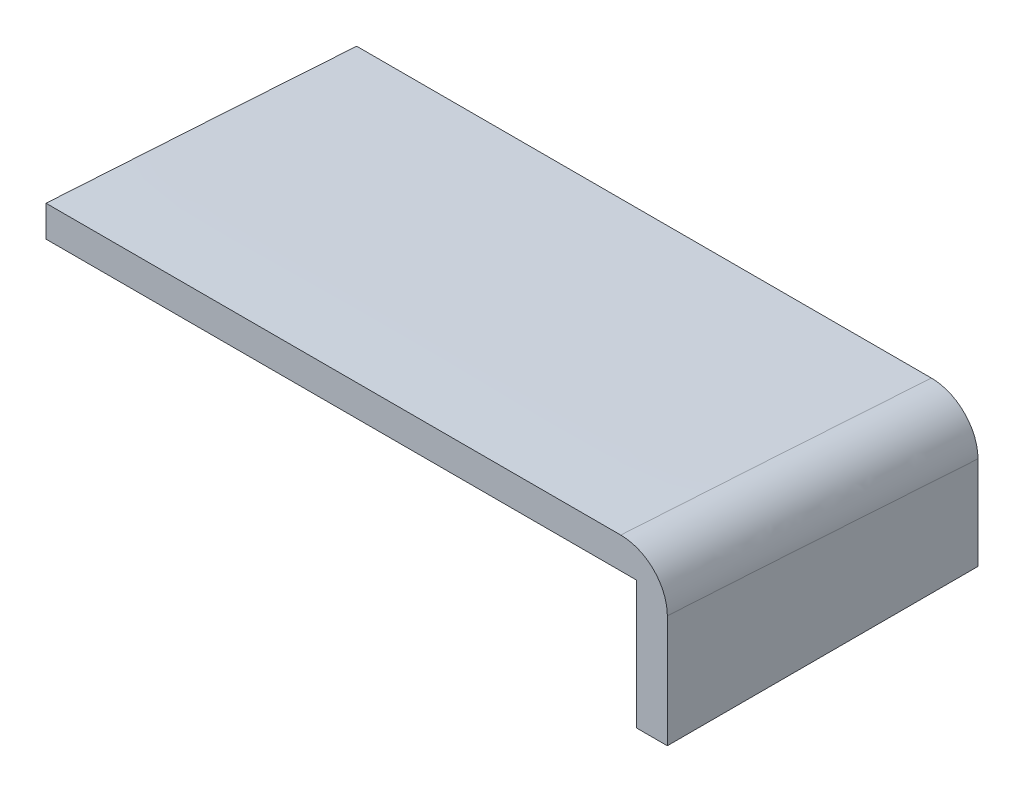
SolidWorks part; units mm, degrees
ref_plane "정면" through (0, 0, 0) normal (0, 0, 1) x (1, 0, 0)
ref_plane "윗면" through (0, 0, 0) normal (0, 1, 0) x (1, 0, 0)
ref_plane "우측면" through (0, 0, 0) normal (1, 0, 0) x (0, 0, -1)
sketch "스케치1" plane through (0, 0, 0) normal (0, 0, 1) x (1, 0, 0)
  line L1 (-40, 50) -> (40, 50)
  line L2 (-40, 50) -> (-40, -50)
  line L3 (-40, -50) -> (40, -50)
  line L4 (40, 50) -> (40, -50)
  line L5 (-40, 50) -> (40, -50) construction
  line L6 (-40, -50) -> (40, 50) construction
  point P0 (0, 0)
  dimension "D1" = 80
  dimension "D2" = 100
extrude "보스-돌출1" add sketch "스케치1" against normal blind 100
sketch "스케치2" plane through (40, 0, 0) normal (1, 0, 0) x (0, 0, -1)
  line L0 (100, -50) -> (100, 50) construction
  line L1 (0, 50) -> (80, 50)
  line L2 (0, 50) -> (0, -35)
  line L3 (0, -35) -> (80, -35)
  line L4 (80, 50) -> (80, -35)
  line L5 (100, -50) -> (0, -50) construction
  dimension "D1" = 20
  dimension "D2" = 15
extrude "컷-돌출1" cut sketch "스케치2" against normal blind 90
sketch "스케치5" plane through (40, 0, 0) normal (1, 0, 0) x (0, 0, -1)
  line L0 (0, -50) -> (0, -35) construction
  line L1 (100, 50) -> (80, 50) construction
  line L2 (96, 50) -> (80, 50)
  line L4 (80, 50) -> (80, -35)
  line L6 (80, -35) -> (0, -35)
  line L8 (80, 50) -> (80, -35)
  line L9 (80, -35) -> (0, -35)
  line L10 (0, -35) -> (0, -50)
  line L11 (0, -50) -> (100, -50)
  line L12 (100, -50) -> (100, 50)
  line L13 (100, 50) -> (80, 50)
  line L15 (80, -35) -> (0, -35)
  line L16 (0, -35) -> (0, -50)
  line L17 (0, -50) -> (100, -50)
  line L18 (100, -50) -> (100, 50)
  line L19 (100, 50) -> (80, 50)
  line L20 (80, 50) -> (80, -35)
  spline S0 degree 3 poles (0, -39.3767) (18.6089, -37.8138) (60.522, -41.4488) (82.6293, -41.815) (94.477, -29.9816) (72.3521, -11.4072) (96, 50) knots 0 0 0 0 0.361872 0.526262 0.755385 1 1 1 1
  dimension "D9" = 9.5231
  dimension "D2" = 22.8534
  dimension "D3" = 11
  dimension "D4" = 8.7853
  dimension "D5" = 36.2853
  dimension "D6" = 13.0435
  dimension "D7" = 22.021
  dimension "D8" = 20
  dimension "D10" = 16
  dimension "D11" = 4.3767
  dimension "D1" = 0
extrude "컷-돌출5" cut sketch "스케치5" against normal through all
shell "쉘2" thickness 2
fillet "필렛1" radius 3 1 edges at (0, 50, -96)
fillet "필렛2" radius 5 1 edges at (0, -39.3767, 0)
fillet "필렛3" radius 3 10 edges at (-40, -47.0329, 0) (-40, -40.6133, -1.3834) (-40, 50, -99.0322) (-40, 49.4694, -96.3609) (40, -47.0329, 0) (40, -40.6133, -1.3834) (40, 50, -99.0322) (40, 49.4694, -96.3609)
ref_plane "평면1" through (40, 47, -98.0645) normal (0, -0.9348, 0.3551) x (-1, 0, 0)
sketch "스케치6" plane through (0, 0, -100) normal (0, 0, -1) x (-1, 0, 0)
  line L0 (-40, -50) -> (-40, 47) construction
  line L1 (-40, -50) -> (-40, 47)
  line L2 (-40, 10) -> (40, 10)
  line L3 (40, 47) -> (40, -50) construction
  line L4 (0, 20.2731) -> (0, 42) construction
  line L5 (-11.9, 11.25) -> (-8.1, 11.25)
  line L6 (-11.9, 11.25) -> (-11.9, 8.75)
  line L7 (-11.9, 8.75) -> (-8.1, 8.75)
  line L8 (-8.1, 11.25) -> (-8.1, 8.75)
  line L9 (-11.9, 11.25) -> (-8.1, 8.75) construction
  line L10 (-11.9, 8.75) -> (-8.1, 11.25) construction
  line L11 (-37, 50) -> (37, 50) construction
  line L12 (11.9, 8.75) -> (8.1, 11.25) construction
  line L13 (11.9, 11.25) -> (8.1, 8.75) construction
  line L14 (8.1, 11.25) -> (8.1, 8.75)
  line L15 (11.9, 8.75) -> (8.1, 8.75)
  line L16 (11.9, 11.25) -> (11.9, 8.75)
  line L17 (11.9, 11.25) -> (8.1, 11.25)
  point P7 (-10, 10)
  point P19 (10, 10)
  dimension "D1" = 3.8
  dimension "D2" = 2.5
  dimension "D3" = 10
  dimension "D4" = 40
extrude "컷-돌출6" cut sketch "스케치6" against normal blind 85 contours L8 L5 L6 L2 | L8 L2 L6 L7 | L16 L2 L14 L15
sketch "스케치8" plane through (0, 50, 0) normal (0, 1, 0) x (1, 0, 0)
  line L0 (-37, 81.3983) -> (-40, 71.8589)
  line L1 (-40, 96) -> (-40, 0) construction
  line L2 (-40, 71.8589) -> (40, 71.8589)
  line L3 (40, 0) -> (40, 96) construction
  line L4 (0, 76.7018) -> (0, 80.7018) construction
  line L5 (-22.5, 71.8589) -> (-17.5, 71.8589)
  line L6 (-22.5, 71.8589) -> (-22.5, 66.8589)
  line L7 (-22.5, 66.8589) -> (-17.5, 66.8589)
  line L8 (-17.5, 71.8589) -> (-17.5, 66.8589)
  line L9 (-22.5, 71.8589) -> (-17.5, 66.8589) construction
  line L10 (-22.5, 66.8589) -> (-17.5, 71.8589) construction
  line L12 (22.5, 66.8589) -> (17.5, 71.8589) construction
  line L13 (22.5, 71.8589) -> (17.5, 66.8589) construction
  line L14 (17.5, 71.8589) -> (17.5, 66.8589)
  line L15 (22.5, 66.8589) -> (17.5, 66.8589)
  line L16 (22.5, 71.8589) -> (22.5, 66.8589)
  line L17 (22.5, 71.8589) -> (17.5, 71.8589)
  point P5 (-20, 69.3589)
  point P14 (0, 71.8589)
  point P20 (20, 69.3589)
  dimension "D1" = 10
  dimension "D2" = 5
  dimension "D3" = 5
  dimension "D4" = 20
extrude "컷-돌출7" cut sketch "스케치8" against normal blind 100 contours L8 L2 L6 L7 | L8 L5 L6 L2 | L16 L17 L14 L2 | L16 L2 L14 L15
sketch "스케치11" plane through (0, 0, -100) normal (0, 0, -1) x (-1, 0, 0)
  line L1 (-22.3234, 3.6269) -> (45.6766, 3.6269) construction
  line L2 (0, 45.5744) -> (0, 67.3013) construction
  line L9 (-37, 50) -> (37, 50) construction
  line L10 (-11, 4.1269) -> (-9, 4.1269)
  line L15 (-11, 4.1269) -> (-11, 3.1269)
  line L16 (-11, 3.1269) -> (-9, 3.1269)
  line L17 (-9, 4.1269) -> (-9, 3.1269)
  line L18 (-11, 4.1269) -> (-9, 3.1269) construction
  line L19 (-11, 3.1269) -> (-9, 4.1269) construction
  line L20 (11, 3.1269) -> (9, 3.1269)
  line L21 (11, 4.1269) -> (11, 3.1269)
  line L22 (11, 4.1269) -> (9, 4.1269)
  line L23 (9, 4.1269) -> (9, 3.1269)
  point P2 (-10, 3.6269)
  dimension "D2" = 2
  dimension "D3" = 1
  dimension "D1" = 46.3731
  dimension "D4" = 10
extrude "컷-돌출8" cut sketch "스케치11" against normal through all
scale "축척1" bodies to scale 119 scale about origin uniform scaling yes scale factor 5
sketch "스케치12" plane through (0, 0, 0) normal (0, 0, 1) x (1, 0, 0)
  line L0 (200, -222.4272) -> (200, 235) construction
  line L1 (-200, 250) -> (200, 250)
  line L2 (-200, 250) -> (-200, -50)
  line L3 (-200, -50) -> (200, -50)
  line L4 (200, 250) -> (200, -50)
  line L5 (-185, 250) -> (185, 250) construction
  line L6 (-200, 235) -> (-200, -222.4272) construction
  line L7 (0, -50) -> (0, -250)
  line L8 (-185, -250) -> (185, -250) construction
  line L9 (0, -250) -> (200, -250)
  line L11 (200, -250) -> (200, -50)
  line L12 (-200, -50) -> (-200, -250)
  line L13 (-200, -250) -> (0, -250)
  line M7 (185, -220.3291) -> (-185, -220.3291)
  line M8 (-185, -220.3291) -> (-185, -250)
  line M9 (-185, -250) -> (185, -250)
  dimension "D1" = 200
extrude "컷-돌출11" cut sketch "스케치12" against normal through all contours L4 L1 L2 L3 | L12 L13 L7 L3 M8 M7 | L7 M7 M8 M9
sketch "스케치15" plane through (0, -250, 0) normal (0, -1, 0) x (1, 0, 0)
  line L0 (200, -200) -> (0, -200)
  line L1 (0, 0) -> (200, 0)
  line L2 (0, 0) -> (0, -500)
  line L3 (0, -500) -> (200, -500)
  line L4 (200, 0) -> (200, -500)
  line L5 (0, -300) -> (200, -300)
  line M4 (185, 0) -> (0, 0)
  line M5 (0, 0) -> (0, -10)
  line M6 (0, -10) -> (190, -10)
  line M7 (190, -10) -> (190, -500)
  line M8 (190, -500) -> (200, -500)
  line M9 (200, -500) -> (200, -15)
  arc M10 (200, -15) -> (185, 0) centre (185, -15) ccw
  dimension "D1" = 200
  dimension "D2" = 100
extrude "컷-돌출13" cut sketch "스케치15" against normal through all contours L2 L0 M6 M7 | L0 M9 M10 M4 M5 M6 M7 | L5 L2 L3 M7 | L5 M7 M8 M9
